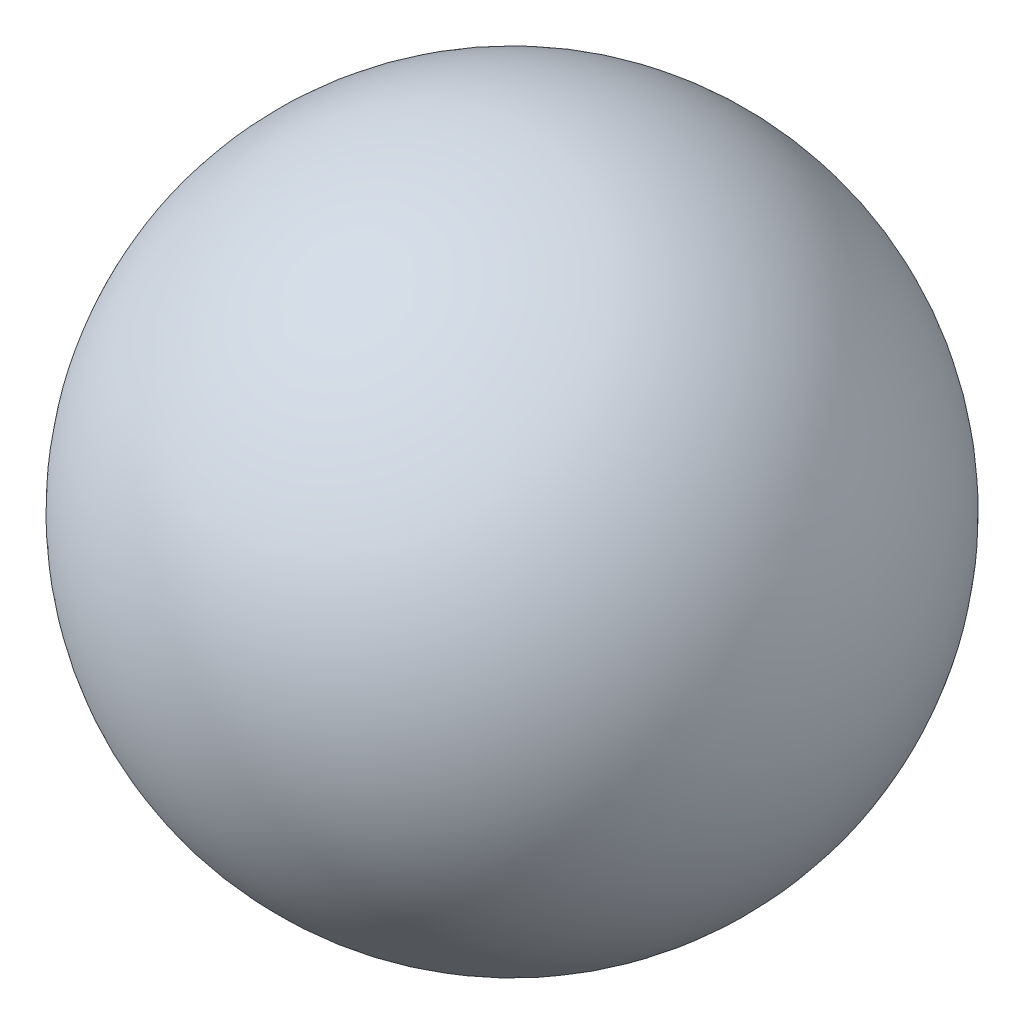
SolidWorks part; units mm, degrees
ref_plane "Front Plane" through (0, 0, 0) normal (0, 0, 1) x (1, 0, 0)
ref_plane "Top Plane" through (0, 0, 0) normal (0, 1, 0) x (1, 0, 0)
ref_plane "Right Plane" through (0, 0, 0) normal (1, 0, 0) x (0, 0, -1)
sketch "Sketch1" plane through (0, 0, 0) normal (0, 0, 1) x (1, 0, 0)
  line L0 (3.21, 0) -> (4.7275, 0)
  line L1 (3.21, 0) -> (4.7275, 0) construction
  arc A0 (4.7275, 0) -> (3.21, 0) centre (3.9688, 0) ccw
revolve "Revolve1" add sketch "Sketch1" angle 360 about L1
